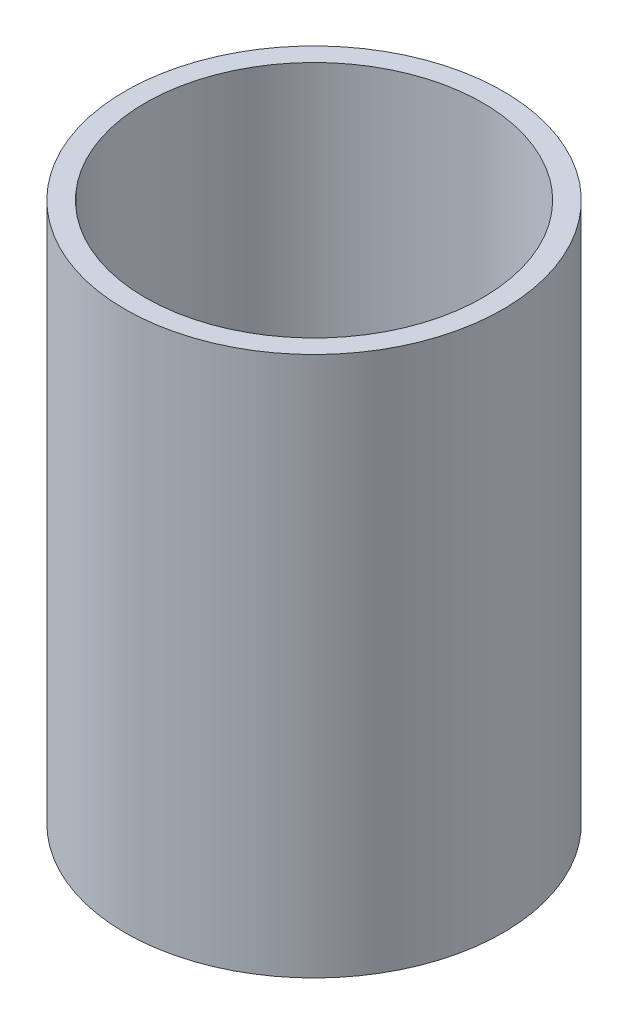
SolidWorks part; units mm, degrees
ref_plane "前视基准面" through (0, 0, 0) normal (0, 0, 1) x (1, 0, 0)
ref_plane "上视基准面" through (0, 0, 0) normal (0, 1, 0) x (1, 0, 0)
ref_plane "右视基准面" through (0, 0, 0) normal (1, 0, 0) x (0, 0, -1)
sketch "草图1" plane through (0, 0, 0) normal (0, 1, 0) x (1, 0, 0)
  circle A0 centre (0, 0) radius 125
  circle A1 centre (0, 0) radius 140
  dimension "D1" = 250
  dimension "D2" = 280
extrude "凸台-拉伸1" add sketch "草图1" along normal blind 400
